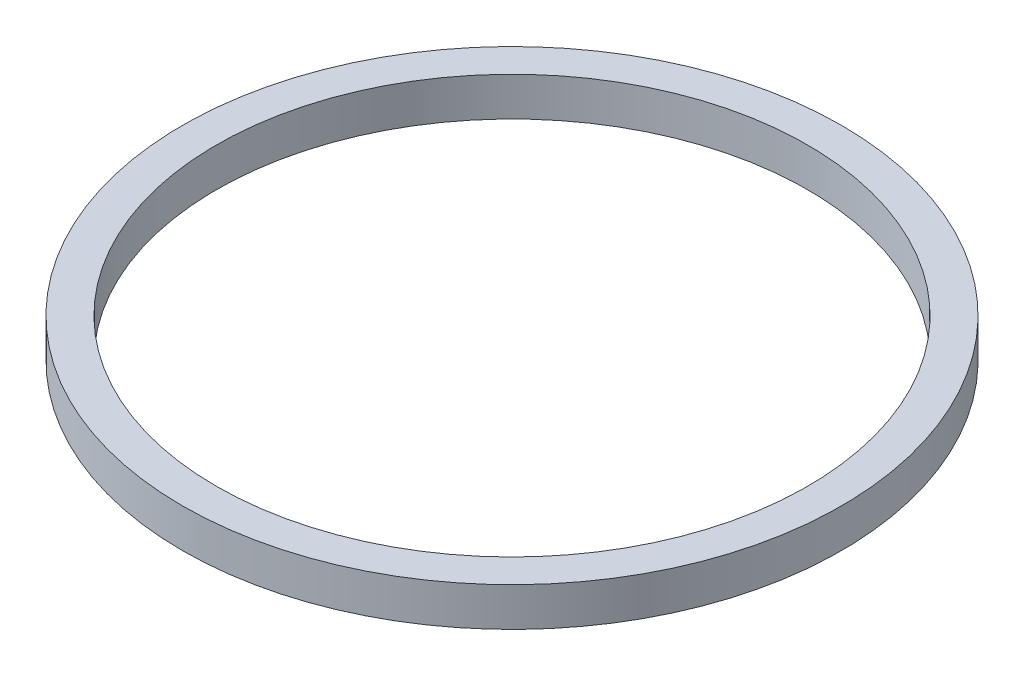
SolidWorks part; units mm, degrees
ref_plane "前视基准面" through (0, 0, 0) normal (0, 0, 1) x (1, 0, 0)
ref_plane "上视基准面" through (0, 0, 0) normal (0, 1, 0) x (1, 0, 0)
ref_plane "右视基准面" through (0, 0, 0) normal (1, 0, 0) x (0, 0, -1)
sketch "草图1" plane through (0, 0, 0) normal (0, 1, 0) x (1, 0, 0)
  circle A0 centre (0, 0) radius 3.05
  circle A1 centre (0, 0) radius 3.4
extrude "凸台-拉伸1" add sketch "草图1" along normal mid plane 0.4 contours A1 | A0
